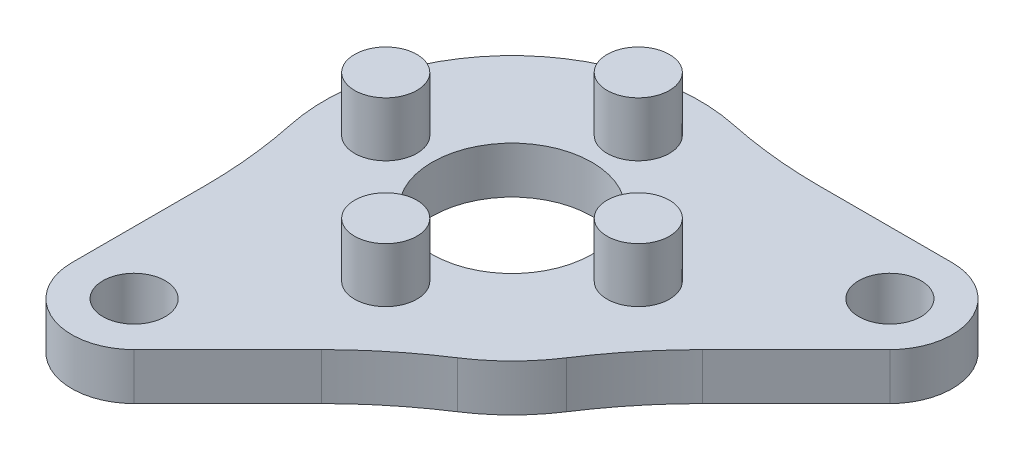
SolidWorks part; units mm, degrees
ref_plane "Front Plane" through (0, 0, 0) normal (0, 0, 1) x (1, 0, 0)
ref_plane "Top Plane" through (0, 0, 0) normal (0, 1, 0) x (1, 0, 0)
ref_plane "Right Plane" through (0, 0, 0) normal (1, 0, 0) x (0, 0, -1)
sketch "Sketch1" plane through (0, 0, 0) normal (0, 1, 0) x (1, 0, 0)
  line L0 (0, 11.1) -> (17.1409, 11.1)
  line L3 (-4.2716, -19.9693) -> (19.9693, 4.2716)
  line L4 (-11.1, 0) -> (-11.1, -17.1409)
  line L9 (0, 0) -> (7.8489, -7.8489) construction
  circle A0 centre (0, 0) radius 11.1 construction
  arc A5 (17.1409, 11.1) -> (19.9693, 4.2716) centre (17.1409, 7.1) cw
  arc A6 (0, 11.1) -> (-11.1, 0) centre (0, 0) ccw
  circle A7 centre (17.1409, 7.1) radius 2
  circle A8 centre (-7.1, -17.1409) radius 2
  arc A9 (-11.1, -17.1409) -> (-4.2716, -19.9693) centre (-7.1, -17.1409) ccw
  circle A10 centre (0, 0) radius 5.125
  dimension "D1" = 22.2
  dimension "D3" = 4
  dimension "D4" = 4
  dimension "D5" = 10.25
  dimension "D2" = 45
extrude "Boss-Extrude2" add sketch "Sketch1" along normal blind 3 contours L4 A9 L3 A5 L0 A6 A8 A7
sketch "Sketch2" plane through (0, 3, 0) normal (0, 1, 0) x (1, 0, 0)
  line L0 (-11.1, 0) -> (15.6978, 0) construction
  line L1 (-4.2716, -19.9693) -> (19.9693, 4.2716) construction
  line L2 (0, 0) -> (7.8489, -7.8489) construction
  line L3 (0, 11.1) -> (0, -15.6978) construction
  circle A0 centre (0, -8.1) radius 2
  circle A1 centre (0, 0) radius 5.125 construction
  circle A2 centre (0, 8.1) radius 2
  circle A3 centre (8.1, 0) radius 2
  circle A4 centre (-8.1, 0) radius 2
  dimension "D1" = 4
  dimension "D2" = 8.1
extrude "Boss-Extrude3" add sketch "Sketch2" along normal blind 3.5
sketch "Sketch3" plane through (0, 3, 0) normal (0, 1, 0) x (1, 0, 0)
  circle A0 centre (0, 0) radius 12
  circle A1 centre (0, 0) radius 11.1
  arc A2 (0, 11.1) -> (-11.1, 0) centre (0, 0) ccw construction
  dimension "D1" = 24
extrude "Boss-Extrude4" add sketch "Sketch3" against normal up to surface (3 mm away) up to face at (0, 0, 5.125)
fillet "Fillet1" radius 30 4 edges at (4.5596, 1.5, -11.1) (4.6248, 1.5, 11.073) (11.073, 1.5, 4.6248) (-11.1, 1.5, 4.5596)
